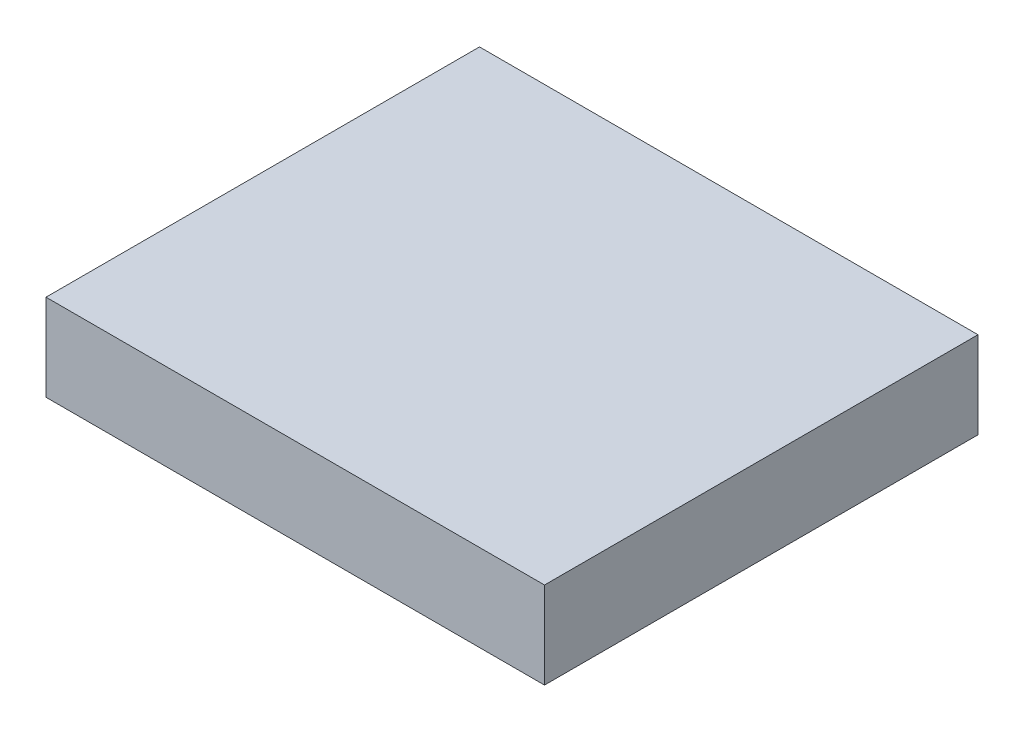
SolidWorks part; units mm, degrees
ref_plane "Front Plane" through (0, 0, 0) normal (0, 0, 1) x (1, 0, 0)
ref_plane "Top Plane" through (0, 0, 0) normal (0, 1, 0) x (1, 0, 0)
ref_plane "Right Plane" through (0, 0, 0) normal (1, 0, 0) x (0, 0, -1)
sketch "Sketch1" plane through (0, 0, 0) normal (0, 1, 0) x (1, 0, 0)
  line L1 (-62.6311, 62.9618) -> (52.3689, 62.9618)
  line L2 (-62.6311, 62.9618) -> (-62.6311, -37.0382)
  line L3 (-62.6311, -37.0382) -> (52.3689, -37.0382)
  line L4 (52.3689, 62.9618) -> (52.3689, -37.0382)
extrude "Boss-Extrude1" add sketch "Sketch1" along normal blind 20
